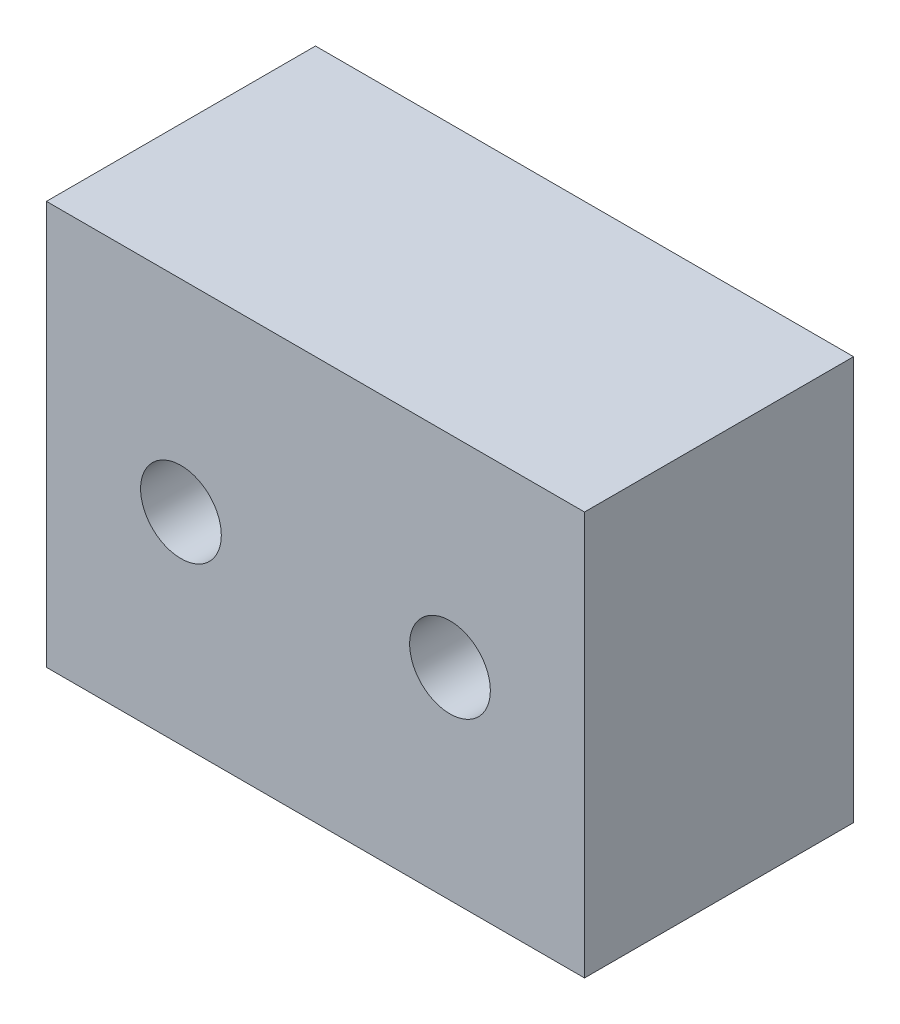
SolidWorks part; units mm, degrees
ref_plane "Front Plane" through (0, 0, 0) normal (0, 0, 1) x (1, 0, 0)
ref_plane "Top Plane" through (0, 0, 0) normal (0, 1, 0) x (1, 0, 0)
ref_plane "Right Plane" through (0, 0, 0) normal (1, 0, 0) x (0, 0, -1)
ref_plane "plane:base-xy" through (0, 0, 0) normal (0, 0, 1) x (1, 0, 0)
sketch "sketch:base-profile" plane through (0, 0, 0) normal (0, 0, 1) x (1, 0, 0)
  line L0 (0, 0) -> (40, 0)
  line L1 (40, 0) -> (40, 30)
  line L2 (40, 30) -> (0, 30)
  line L3 (0, 30) -> (0, 0)
extrude "feature:base" add sketch "sketch:base-profile" along normal blind 20 separate body
ref_plane "plane:top-xy" through (0, 0, 20) normal (0, 0, 1) x (1, 0, 0)
sketch "sketch:holes-profile" plane through (0, 0, 20) normal (0, 0, 1) x (1, 0, 0)
  circle A0 centre (10, 15) radius 3
  circle A1 centre (30, 15) radius 3
extrude "feature:two-holes" cut sketch "sketch:holes-profile" against normal through all
